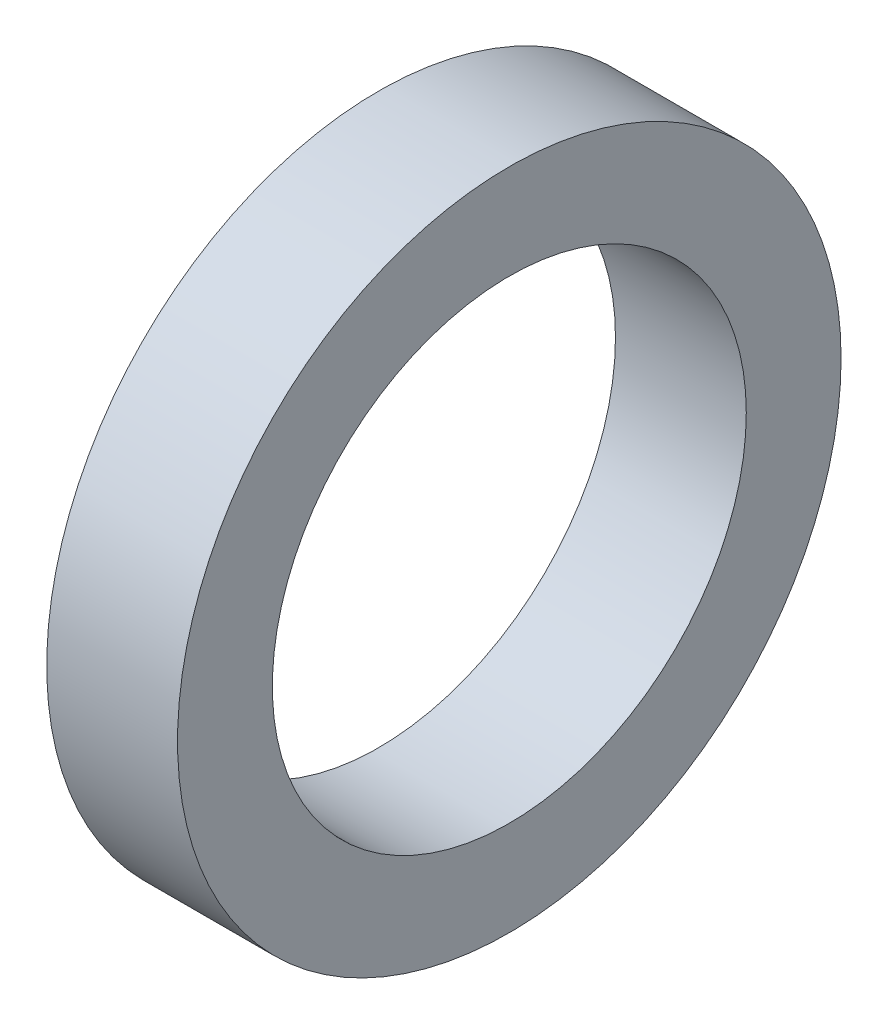
SolidWorks part; units mm, degrees
material "6061-T6 (SS)"
ref_plane "Front Plane" through (0, 0, 0) normal (0, 0, 1) x (1, 0, 0)
ref_plane "Top Plane" through (0, 0, 0) normal (0, 1, 0) x (1, 0, 0)
ref_plane "Right Plane" through (0, 0, 0) normal (1, 0, 0) x (0, 0, -1)
sketch "Sketch1" plane through (0, 0, 0) normal (1, 0, 0) x (0, 0, -1)
  circle A0 centre (0, 0) radius 8.89
  circle A1 centre (0, 0) radius 6.35
  dimension "D1" = 12.7
  dimension "D2" = 17.78
extrude "Boss-Extrude1" add sketch "Sketch1" along normal blind 3.5052
